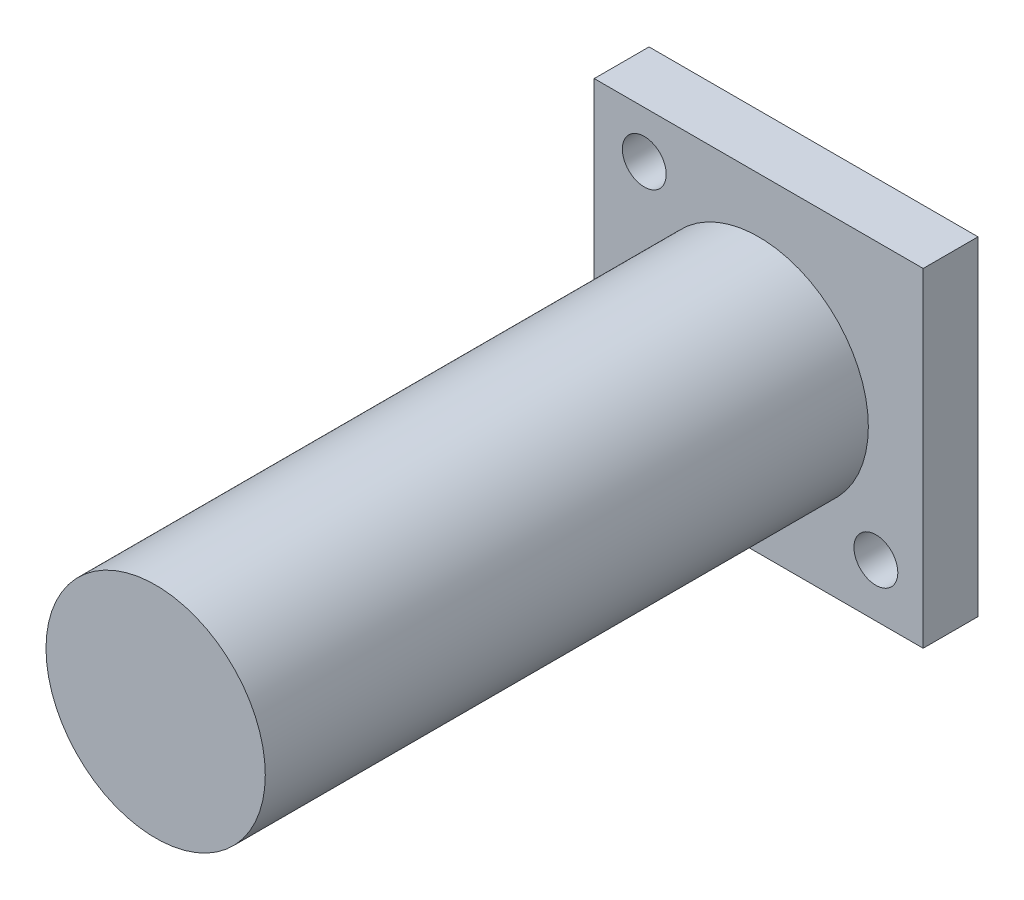
SolidWorks part; units mm, degrees
ref_plane "Front Plane" through (0, 0, 0) normal (0, 0, 1) x (1, 0, 0)
ref_plane "Top Plane" through (0, 0, 0) normal (0, 1, 0) x (1, 0, 0)
ref_plane "Right Plane" through (0, 0, 0) normal (1, 0, 0) x (0, 0, -1)
sketch "Sketch1" plane through (0, 0, 0) normal (0, 0, 1) x (1, 0, 0)
  line L1 (-13, -13) -> (13, -13)
  line L2 (-13, -13) -> (-13, 13)
  line L3 (-13, 13) -> (13, 13)
  line L4 (13, -13) -> (13, 13)
  line L5 (-13, -13) -> (13, 13) construction
  line L6 (-13, 13) -> (13, -13) construction
  circle A0 centre (0, 0) radius 10
  dimension "D1" = 20
  dimension "D2" = 13
  dimension "D3" = 13
extrude "Boss-Extrude1" add sketch "Sketch1" along normal blind 60 contours A0
sketch "Sketch3" plane through (0, 0, 0) normal (0, 0, -1) x (-1, 0, 0)
  line L1 (-15, -15) -> (15, -15)
  line L2 (-15, -15) -> (-15, 15)
  line L3 (-15, 15) -> (15, 15)
  line L4 (15, -15) -> (15, 15)
  line L5 (-15, -15) -> (15, 15) construction
  line L6 (-15, 15) -> (15, -15) construction
  circle A0 centre (0, 0) radius 10 construction
  point P0 (0, 0)
  dimension "D1" = 15
  dimension "D2" = 15
extrude "Boss-Extrude2" add sketch "Sketch3" against normal blind 5
hole_wizard "Ø4.0mm Dowel Hole1" positions "3DSketch2" profile "Sketch5" hole size "Ø4.0" standard "ANSI Metric"
sketch3d "3DSketch2"
  point P0 (-10.4335, 10.716, 5)
  point P4 (10.6871, -10.1839, 5)
  point P9 (10.5399, 10.6424, 3)
sketch "Sketch5" plane through (-10.4335, 10.716, 5) normal (1, 0, 0) x (0, -1, 0)
  line L0 (0, 0) -> (0, 36.2017)
  line L1 (0, 36.2017) -> (2, 35)
  line L2 (2, 35) -> (2, 0)
  line L5 (2, 0) -> (0, 0)
  line L10 (0, 36.2017) -> (-2, 35) construction
  line L11 (0, -6.35) -> (0, 107.95) construction
  dimension "Hole Dia." = 4
  dimension "Hole Depth" = 35
  dimension "Drill Angle" = 118
